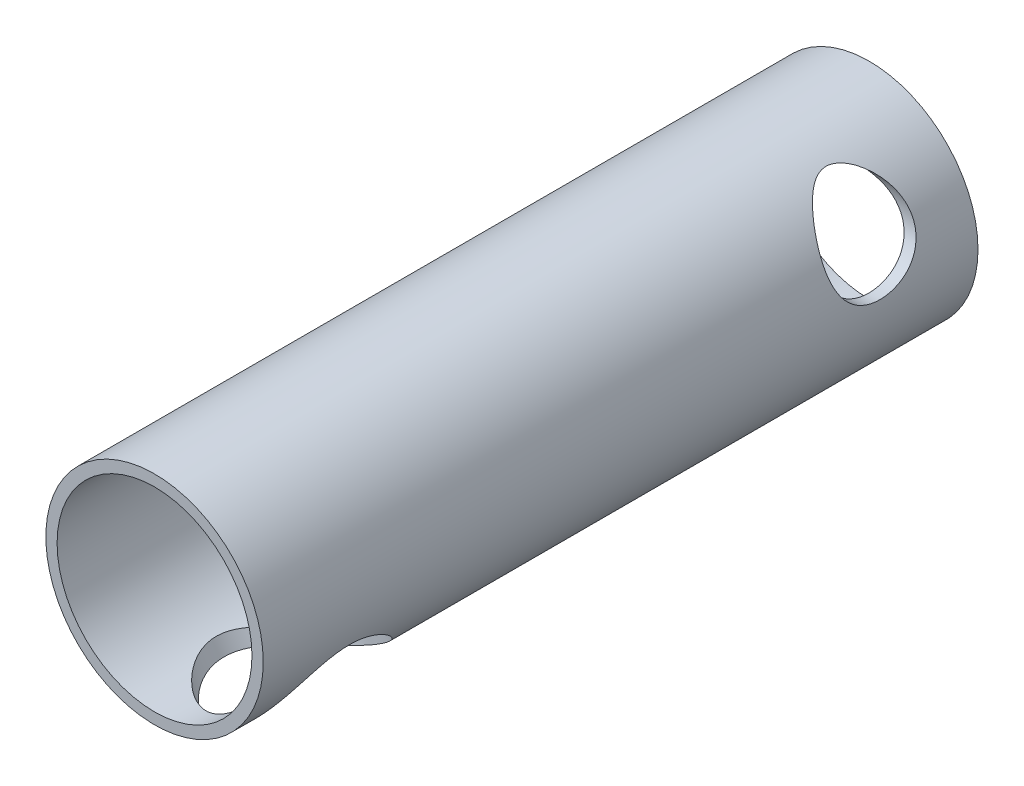
SolidWorks part; units mm, degrees
ref_plane "Front Plane" through (0, 0, 0) normal (0, 0, 1) x (1, 0, 0)
ref_plane "Top Plane" through (0, 0, 0) normal (0, 1, 0) x (1, 0, 0)
ref_plane "Right Plane" through (0, 0, 0) normal (1, 0, 0) x (0, 0, -1)
sketch "Sketch1" plane through (0, 0, 0) normal (0, 0, 1) x (1, 0, 0)
  line L0 (-0.0494, 0) -> (-22.2407, -0.9122)
  circle A0 centre (-0.0494, 0) radius 22.21
  circle A1 centre (-0.0494, 0) radius 19.91
  point P4 (-13.1198, -17.9569)
  dimension "D1" = 44.42
  dimension "D2" = 39.82
extrude "Boss-Extrude1" add sketch "Sketch1" along normal blind 146.05
sketch "Sketch2" plane through (0, 0, 146.05) normal (0, 0, 1) x (1, 0, 0)
  line L0 (0, 0) -> (11.0926, -19.213)
  line L1 (0, 0) -> (22.1606, 0)
  circle A1 centre (-0.0494, 0) radius 22.21 construction
  dimension "D1" = 60
ref_plane "Plane1" through (11.0926, -19.213, 146.05) normal (0.5017, -0.8651, 0) x (-0.8651, -0.5017, 0)
ref_plane "Plane2" through (22.1606, 0, 146.05) normal (1, 0, 0) x (0, 0, -1)
sketch "Sketch4" plane through (22.1606, 0, 146.05) normal (1, 0, 0) x (0, 0, -1)
  line L0 (146.05, -22.21) -> (146.05, 22.21) construction
  line L1 (146.05, 22.21) -> (0, 22.21) construction
  circle A0 centre (126.05, 10.1535) radius 9.0424
  dimension "D1" = 18.0848
  dimension "D2" = 20
  dimension "D3" = 12.0565
sketch "Sketch5" plane through (11.0926, -19.213, 146.05) normal (0.5017, -0.8651, 0) x (-0.8651, -0.5017, 0)
  line L0 (-0.0428, 0) -> (-19.213, 0) construction
  circle A0 centre (-0.0494, 18.7) radius 14.8463
  dimension "D1" = 29.6926
  dimension "D2" = 18.7
extrude "Cut-Extrude2" cut sketch "Sketch5" against normal up to next contours A0
extrude "Cut-Extrude3" cut sketch "Sketch4" against normal up to next contours A0
equation "\"can_outer_diameter\"= 44.42mm"
equation "\"D1@Sketch1\"=\"can_outer_diameter\""
equation "\"can_thickness\"= 2.3"
equation "\"D2@Sketch1\"=\"can_outer_diameter\"-2*\"can_thickness\""
equation "\"can_height\"= 5.75in"
equation "\"D1@Boss-Extrude1\"=\"can_height\""
equation "\"inlet_diameter\"= 0.712in"
equation "\"D1@Sketch4\"=\"inlet_diameter\""
equation "\"outlet_diameter\" = 1.169in"
equation "\"D1@Sketch5\"=\"outlet_diameter\""
equation "\"D2@Sketch5\"=6mm+12.7"
equation "\"D3@Sketch4\"=\"inlet_diameter\"/1.5"
